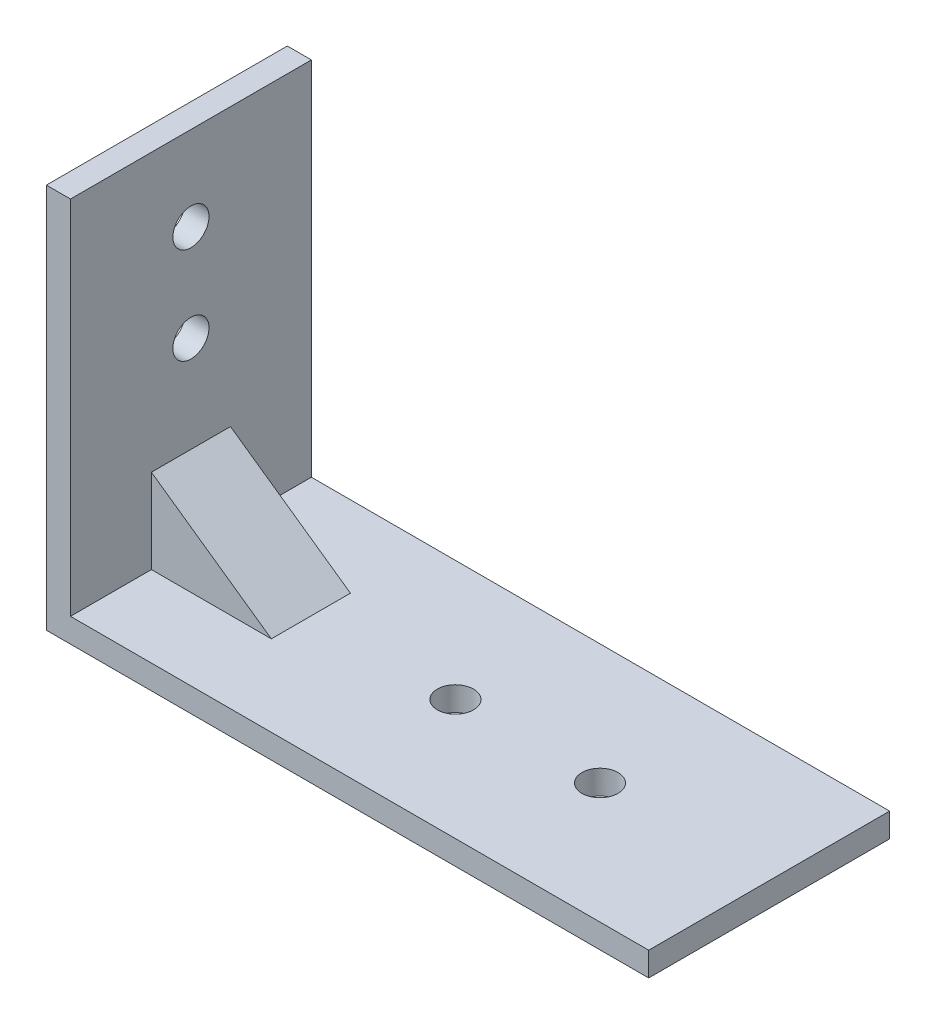
SolidWorks part; units mm, degrees
ref_plane "Front Plane" through (0, 0, 0) normal (0, 0, 1) x (1, 0, 0)
ref_plane "Top Plane" through (0, 0, 0) normal (0, 1, 0) x (1, 0, 0)
ref_plane "Right Plane" through (0, 0, 0) normal (1, 0, 0) x (0, 0, -1)
sketch "Sketch1" plane through (0, 0, 0) normal (0, 1, 0) x (1, 0, 0)
  line L1 (0, 0) -> (50, 0)
  line L2 (0, 0) -> (0, 20)
  line L3 (0, 20) -> (50, 20)
  line L4 (50, 0) -> (50, 20)
  dimension "D1" = 20
  dimension "D2" = 50
extrude "Boss-Extrude1" add sketch "Sketch1" along normal blind 2
sketch "Sketch2" plane through (0, 2, 0) normal (0, 1, 0) x (1, 0, 0)
  line L0 (0, 0) -> (50, 0) construction
  line L1 (0, 20) -> (2, 20)
  line L2 (0, 20) -> (0, 0)
  line L3 (0, 0) -> (2, 0)
  line L4 (2, 20) -> (2, 0)
  dimension "D1" = 2
extrude "Boss-Extrude2" add sketch "Sketch2" along normal blind 30
sketch "Sketch4" plane through (0, 2, 0) normal (0, 1, 0) x (1, 0, 0)
  line L0 (2, 20) -> (2, 0) construction
  line L2 (2, 13.2848) -> (11.9554, 13.2848)
  line L3 (2, 13.2848) -> (2, 6.72)
  line L4 (2, 6.72) -> (11.9554, 6.72)
  line L5 (11.9554, 13.2848) -> (11.9554, 6.72)
  point P4 (2, 10)
  dimension "D1" = 3.2848
  dimension "D2" = 3.28
  dimension "D3" = 9.9554
extrude "Boss-Extrude3" add sketch "Sketch4" along normal blind 7
sketch "Sketch5" plane through (0, 0, -6.72) normal (0, 0, 1) x (1, 0, 0)
  line L0 (2, 9) -> (11.9554, 2)
  line L1 (11.9554, 2) -> (11.9554, 9)
  line L2 (11.9554, 9) -> (2, 9)
extrude "Cut-Extrude1" cut sketch "Sketch5" against normal blind 7
sketch "Sketch6" plane through (0, 2, 0) normal (0, 1, 0) x (1, 0, 0)
  line L0 (2, 10) -> (50, 10) construction
  line L1 (2, 0) -> (2, 20) construction
  line L2 (50, 0) -> (50, 20) construction
  line L4 (11.9554, 6.72) -> (11.9554, 13.2848) construction
  circle A0 centre (23.9554, 10) radius 1.5
  circle A1 centre (35.9554, 10) radius 1.5
  dimension "D1" = 12
  dimension "D2" = 12
  dimension "D3" = 3
  dimension "D4" = 3
extrude "Cut-Extrude2" cut sketch "Sketch6" against normal blind 7
sketch "Sketch7" plane through (2, 0, 0) normal (1, 0, 0) x (0, 0, -1)
  line L0 (13.2848, 9) -> (6.72, 9) construction
  line L1 (0, 32) -> (20, 32) construction
  line L2 (10.0024, 9) -> (10, 32) construction
  circle A0 centre (10.0016, 17) radius 1.5
  circle A1 centre (10.0007, 25) radius 1.5
  dimension "D1" = 8
  dimension "D2" = 8
  dimension "D3" = 3
  dimension "D4" = 3
extrude "Cut-Extrude3" cut sketch "Sketch7" against normal blind 7
